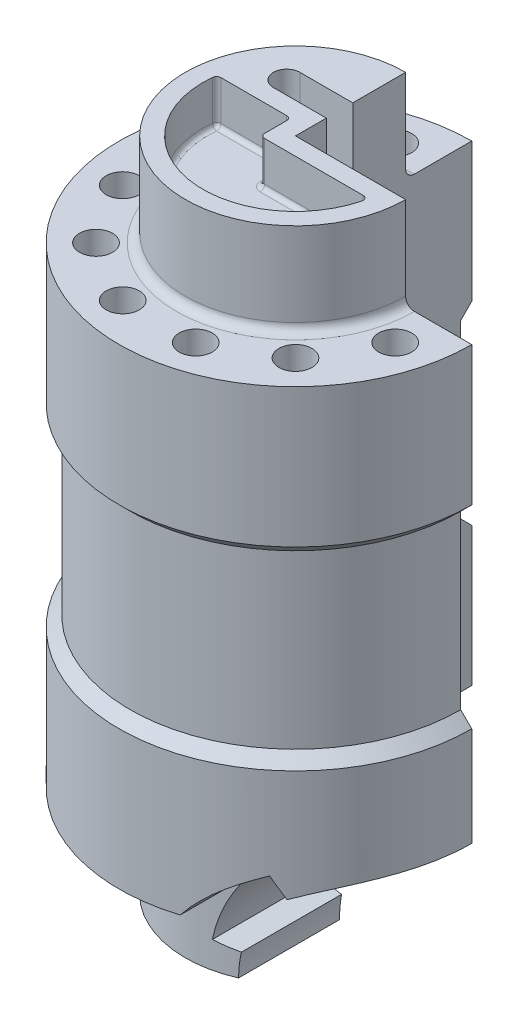
SolidWorks part; units mm, degrees
material "AISI 1020"
ref_plane "Front Plane" through (0, 0, 0) normal (0, 0, 1) x (1, 0, 0)
ref_plane "Top Plane" through (0, 0, 0) normal (0, 1, 0) x (1, 0, 0)
ref_plane "Right Plane" through (0, 0, 0) normal (1, 0, 0) x (0, 0, -1)
sketch "Sketch1" plane through (0, 0, 0) normal (0, 1, 0) x (1, 0, 0)
  circle A0 centre (0, 0) radius 40
  dimension "D1" = 80
extrude "Boss-Extrude1" add sketch "Sketch1" along normal mid plane 149
sketch "Sketch3" plane through (0, 74.5, 0) normal (0, 1, 0) x (1, 0, 0)
  circle A0 centre (0, 0) radius 25
  circle A1 centre (0, 0) radius 40 construction
  circle A2 centre (0, 0) radius 40
  dimension "D1" = 50
extrude "Cut-Extrude1" cut sketch "Sketch3" against normal blind 21 contours A2 | A0
mirror "Mirror1" about plane through (0, 0, 0) normal (0, 1, 0) of "Cut-Extrude1"
sketch "Sketch2" plane through (0, 0, 0) normal (0, 1, 0) x (1, 0, 0)
  circle A0 centre (0, 0) radius 37.5
  circle A1 centre (0, 0) radius 40 construction
  circle A2 centre (0, 0) radius 40
  dimension "D1" = 75
extrude "Cut-Extrude2" cut sketch "Sketch2" along normal offset from surface 31.5 and the other way offset from surface (22 mm away) 31.5 up to face at (0, 53.5, 25) other way up to face at (0, -53.5, 40)
sketch "Sketch5" plane through (0, 74.5, 0) normal (0, 1, 0) x (1, 0, 0)
  line L0 (0, -53.6027) -> (0, 7) construction
  line L1 (-43.3294, 0) -> (45.1465, 0) construction
  line L2 (-12, 10) -> (12, 10) construction
  line L3 (-12, 13) -> (12, 13)
  line L4 (-12, 7) -> (12, 7)
  line L6 (0, 13) -> (0, 49.2698) construction
  arc A0 (-12, 13) -> (-12, 7) centre (-12, 10) ccw
  arc A1 (12, 7) -> (12, 13) centre (12, 10) ccw
  point P7 (0, 10)
  dimension "D1" = 3
  dimension "D2" = 12
  dimension "D3" = 7
extrude "Cut-Extrude4" cut sketch "Sketch5" against normal through all
fillet "Fillet1" radius 2 2 edges at (0, -53.5, 25) (0, 53.5, 25)
chamfer "Chamfer1" [suppressed] distance 2.5 angle 45
sketch "Sketch7" plane through (0, 0, 0) normal (1, 0, 0) x (0, 0, -1)
  line L0 (40, 22) -> (37.5, 19.5)
  line L1 (37.5, -22) -> (37.5, 22) construction
  line L2 (40, 22) -> (40, 53.5) construction
  line L3 (40, 22) -> (37.5, 22)
  line L4 (37.5, 22) -> (37.5, 19.5)
  line L5 (0, 103.8814) -> (0, -88.9255) construction
  dimension "D1" = 45
  dimension "D2" = 2.5
revolve "Revolve2" add sketch "Sketch7" angle 360 about L5
mirror "Mirror2" about plane through (0, 0, 0) normal (0, 1, 0) of "Revolve2"
sketch "Sketch4" plane through (0, 74.5, 0) normal (0, 1, 0) x (1, 0, 0)
  line L0 (0, 0) -> (0, 40)
  line L1 (0, 0) -> (40, 0)
  circle A0 centre (0, 0) radius 40 construction
  arc A1 (40, 0) -> (0, 40) centre (0, 0) ccw
extrude "Cut-Extrude5" cut sketch "Sketch4" against normal through all
sketch "Sketch8" plane through (0, 53.5, 0) normal (0, 1, 0) x (1, 0, 0)
  line L0 (0, -45.9152) -> (0, 46.8029) construction
  line L1 (-43.3294, 0) -> (43.4692, 0) construction
  line L2 (0, 0) -> (-12.5822, 46.9576) construction
  line L3 (0, 0) -> (43.6258, -11.6895) construction
  line L4 (0, 0) -> (22.6274, -22.6274) construction
  line L5 (0, 0) -> (10.3528, -38.637) construction
  line L6 (0, 0) -> (-8.2822, -30.9096) construction
  line L7 (0, 0) -> (-22.6274, -22.6274) construction
  line L8 (0, 0) -> (-30.9096, -8.2822) construction
  line L9 (0, 0) -> (-30.9096, 8.2822) construction
  line L10 (0, 0) -> (-22.6274, 22.6274) construction
  circle A1 centre (0, 0) radius 32 construction
  circle A3 centre (-8.2822, 30.9096) radius 3.75
  circle A4 centre (30.9096, -8.2822) radius 3.75
  circle A5 centre (22.6274, -22.6274) radius 3.75
  circle A12 centre (16.353, 18.0359) radius 3.75 [skipped]
  circle A13 centre (-0.2003, 18.6445) radius 3.75 [skipped]
  circle A14 centre (-13.2094, 8.3907) radius 3.75 [skipped]
  circle A15 centre (-16.4846, -7.8468) radius 3.75 [skipped]
  circle A16 centre (-8.4673, -22.3417) radius 3.75 [skipped]
  circle A17 centre (7.0275, -28.1973) radius 3.75 [skipped]
  arc A18 (0, 40) -> (40, 0) centre (0, 0) ccw construction
  circle A19 centre (8.2822, -30.9096) radius 3.75
  circle A20 centre (-8.2822, -30.9096) radius 3.75
  circle A22 centre (-22.6274, -22.6274) radius 3.75
  circle A23 centre (-30.9096, -8.2822) radius 3.75
  circle A24 centre (-30.9096, 8.2822) radius 3.75
  circle A25 centre (-22.6274, 22.6274) radius 3.75
  point P28 (-11.024, -34.0902)
  point P29 (0, 0)
  point P30 (0, 0)
  point P51 (0, 0)
  point P52 (0, 0)
  point P53 (-9.128, -25.4102)
  point P54 (-8.2822, -25.6824)
  point P55 (0, 0)
  dimension "D2" = 64
  dimension "D3" = 7.5
  dimension "D1" = 15
  dimension "D4" = 15
  dimension "D6" = 30
  dimension "D7" = 30
  dimension "D8" = 15
  dimension "D9" = 30
  dimension "D10" = 30
  dimension "D11" = 30
  dimension "D12" = 30
  dimension "D5" = 8
extrude "Cut-Extrude6" cut sketch "Sketch8" against normal through all
sketch "Sketch10" plane through (0, 0, 0) normal (0, 0, -1) x (-1, 0, 0)
  line L0 (-10, -74.5) -> (-64.1408, -74.5) construction
  line L1 (-40, -44.5) -> (-40, -97.186) construction
  line L2 (-40, -53.5) -> (-40, -22) construction
  line L3 (-27.3215, -47.3108) -> (-25.2084, -42.7792)
  line L4 (-10.4558, -69.2906) -> (-5.5317, -68.4223)
  line L5 (-40, -53.5) -> (-40, -44.5)
  line L6 (-40, -53.5) -> (-27, -53.5) construction
  line L7 (-40, -53.5) -> (-27, -53.5)
  line L8 (-25, -74.5) -> (-25, -55.5) construction
  line L9 (-25, -74.5) -> (-25, -55.5)
  line L10 (-27.3215, -47.3108) -> (-40, -74.5) construction
  line L11 (-10.4558, -69.2906) -> (-40, -74.5) construction
  line L22 (-25, -74.5) -> (0, -74.5)
  line L23 (0, -74.5) -> (0, 74.5)
  line L24 (0, 74.5) -> (-25, 74.5)
  line L25 (-25, 74.5) -> (-25, 55.5)
  line L26 (-27, 53.5) -> (-40, 53.5)
  line L27 (-40, 53.5) -> (-40, 22)
  line L28 (-40, 22) -> (-37.5, 19.5)
  line L29 (-37.5, 19.5) -> (-37.5, -19.5)
  line L30 (-37.5, -19.5) -> (-40, -22)
  line L31 (-40, -22) -> (-40, -53.5)
  line L32 (-40, -53.5) -> (-27, -53.5)
  line L33 (-25, -55.5) -> (-25, -74.5)
  line L34 (-25, -74.5) -> (-10, -74.5)
  line L43 (-40, -44.5) -> (-40, -53.5)
  line L44 (-40, -53.5) -> (-27, -53.5)
  line L45 (-25, -55.5) -> (-25, -74.5)
  arc A2 (-5.5317, -68.4223) -> (-25.2084, -42.7792) centre (-40, -74.5) ccw
  arc A3 (-10, -74.5) -> (-10.4558, -69.2906) centre (-40, -74.5) ccw
  arc A4 (-25, -55.5) -> (-27, -53.5) centre (-27, -55.5) ccw construction
  arc A5 (-25, -55.5) -> (-27, -53.5) centre (-27, -55.5) ccw
  arc A6 (-27.3215, -47.3108) -> (-40, -44.5) centre (-40, -74.5) ccw
  arc A8 (-27, 53.5) -> (-25, 55.5) centre (-27, 55.5) ccw
  arc A9 (-25, -55.5) -> (-27, -53.5) centre (-27, -55.5) ccw
  arc A11 (-25, -55.5) -> (-27, -53.5) centre (-27, -55.5) ccw
  point P17 (0, 0)
  line M23 (-25, -74.5) -> (0, -74.5)
  line M33 (-40, -22) -> (-40, -53.5)
  line M34 (-40, -53.5) -> (-27, -53.5)
  arc M35 (-27, -53.5) -> (-25, -55.5) centre (-27, -55.5) cw
  line M36 (-25, -55.5) -> (-25, -74.5)
  dimension "D1" = 70
  dimension "D2" = 60
  dimension "D6" = 5
  dimension "D3" = 25
  dimension "D4" = 10
  dimension "D5" = 0
extrude "Cut-Extrude7" cut sketch "Sketch10" against normal through all contours L3 A6 A3 L4 A2 M33 M34 M35 M36 M23
sketch "Sketch11" plane through (0, 74.5, 0) normal (0, 1, 0) x (1, 0, 0)
  line L2 (-20.7846, 3) -> (-4, 3)
  line L3 (-4, 3) -> (-4, -4)
  line L4 (-4, -4) -> (20.6155, -4)
  line L5 (-12, 7) -> (0, 7) construction
  line L6 (0, 0) -> (25, 0) construction
  line L7 (0, 7) -> (0, 0) construction
  arc A4 (0, 21) -> (21, 0) centre (0, 0) ccw
  arc A5 (-20.7846, 3) -> (20.6155, -4) centre (0, 0) ccw
  dimension "D2" = 4
  dimension "D3" = 4
  dimension "D4" = 4
  dimension "D1" = 4
extrude "Cut-Extrude8" cut sketch "Sketch11" against normal blind 10
fillet "Fillet2" radius 1 4 edges at (-20.7846, 69.5, -3) (-4, 69.5, -3) (-4, 69.5, 4) (20.6155, 69.5, 4)
fillet "Fillet3" radius 1 8 edges at (-20.5706, 64.5, -2.7416) (-12.4499, 64.5, -3) (-4.2929, 64.5, -2.7071) (-4, 64.5, 0.5) (-3.7071, 64.5, 3.7071) (8.1825, 64.5, 4) (20.1555, 64.5, 4.3876) (-3.6857, 64.5, 20.674)
fillet "Fillet4" [suppressed] radius 1
fillet "Fillet5" [suppressed] radius 1
equation "\"A\"= 149"
equation "\"B\"= 21"
equation "\"C\" = 31.5"
equation "\"D1@Boss-Extrude1\"=\"A\""
equation "\"D1@Cut-Extrude1\"=\"B\""
equation "\"D1@Cut-Extrude2\"=\"C\""
equation "\"D2@Cut-Extrude2\"=\"C\""
equation "\"D7@Sketch8\"=\"D6@Sketch8\""
equation "\"D8@Sketch8\"=\"D1@Sketch8\""
equation "\"D9@Sketch8\"=\"D6@Sketch8\""
equation "\"D10@Sketch8\"=\"D6@Sketch8\""
equation "\"D11@Sketch8\"=\"D6@Sketch8\""
equation "\"D12@Sketch8\"=\"D6@Sketch8\""
equation "\"D4@Sketch8\"=\"D1@Sketch8\""
